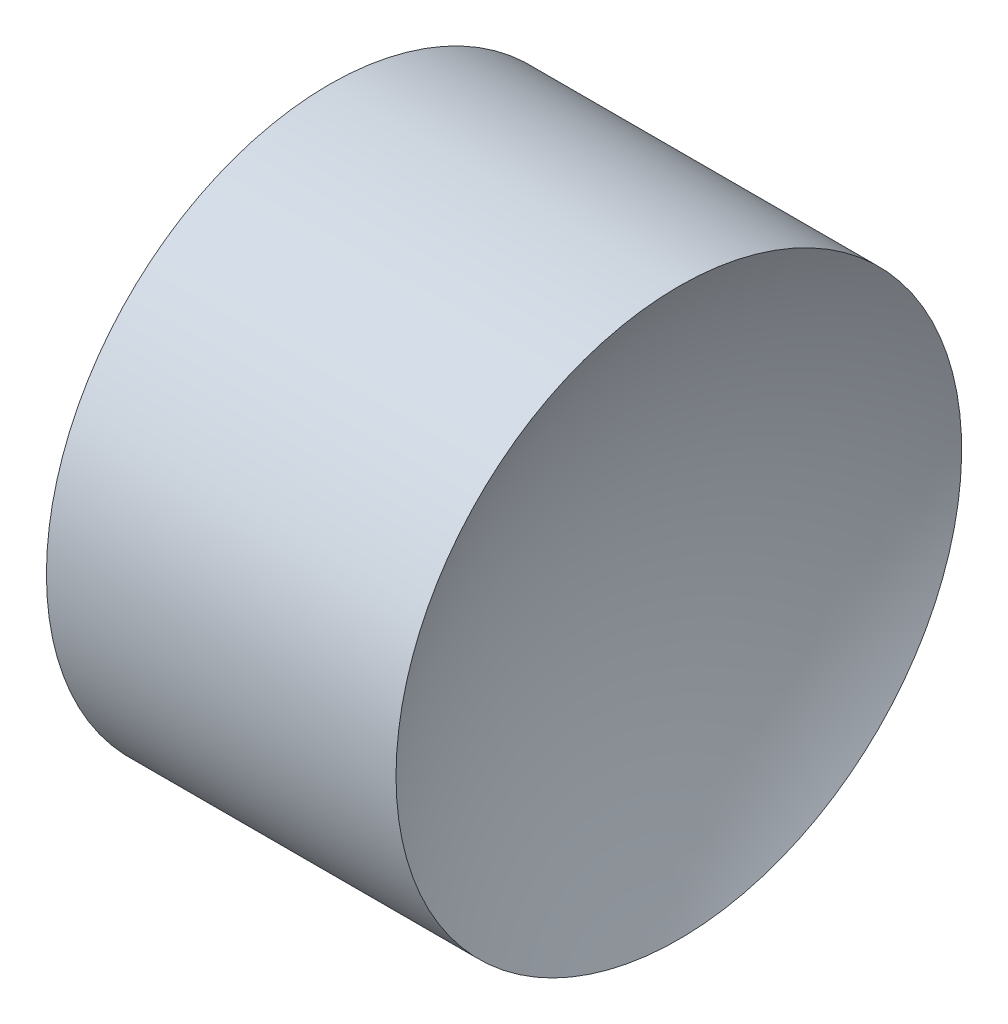
SolidWorks part; units mm, degrees
material "玻璃"
ref_plane "前视基准面" through (0, 0, 0) normal (0, 0, 1) x (1, 0, 0)
ref_plane "上视基准面" through (0, 0, 0) normal (0, 1, 0) x (1, 0, 0)
ref_plane "右视基准面" through (0, 0, 0) normal (1, 0, 0) x (0, 0, -1)
sketch "草图1" plane through (0, 0, 0) normal (0, 0, 1) x (1, 0, 0)
  line L0 (0.2085, 0) -> (0.6322, 0)
  line L1 (0.8035, 0.65) -> (0.6069, 0.65)
  line L2 (0, 0.65) -> (0.8035, 0.65)
  arc A0 (0.2085, 0) -> (0, 0.65) centre (-0.9087, 0) ccw
  arc A1 (0.8035, 0.65) -> (0.6322, 0) centre (1.9509, 0) ccw
revolve "旋转1" add sketch "草图1" angle 360 about L0
